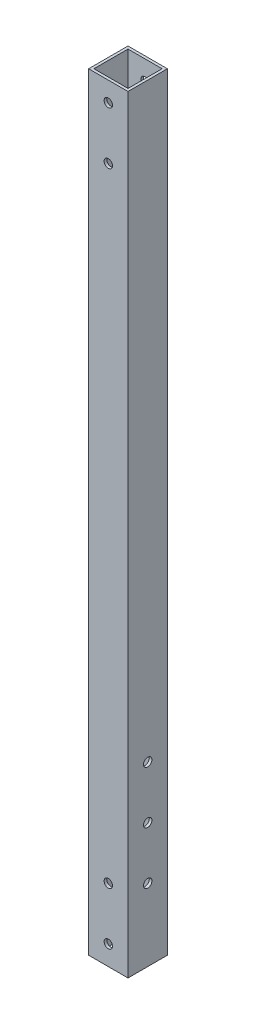
SolidWorks part; units mm, degrees
ref_plane "前视基准面" through (0, 0, 0) normal (0, 0, 1) x (1, 0, 0)
ref_plane "上视基准面" through (0, 0, 0) normal (0, 1, 0) x (1, 0, 0)
ref_plane "右视基准面" through (0, 0, 0) normal (1, 0, 0) x (0, 0, -1)
sketch "草图1" plane through (0, 0, 0) normal (0, 1, 0) x (1, 0, 0)
  line L1 (-7.5, -7.5) -> (7.5, -7.5)
  line L2 (-7.5, -7.5) -> (-7.5, 7.5)
  line L3 (-7.5, 7.5) -> (7.5, 7.5)
  line L4 (7.5, -7.5) -> (7.5, 7.5)
  line L5 (-7.5, -7.5) -> (7.5, 7.5) construction
  line L6 (-7.5, 7.5) -> (7.5, -7.5) construction
  point P0 (0, 0)
  dimension "D1" = 15
  dimension "D2" = 15
extrude "拉伸-薄壁1" add sketch "草图1" along normal blind 292.5 thin thin type one direction reverse wall 1
sketch "草图2" plane through (0, 0, 7.5) normal (0, 0, 1) x (1, 0, 0)
  line L0 (0, 0) -> (0, 292.5) construction
  line L1 (-7.5, 292.5) -> (7.5, 292.5) construction
  line L2 (-1000, 146.25) -> (49000, 146.25) construction
  line L3 (-7.5, 0) -> (7.5, 0) construction
  circle A0 centre (0, 7.5) radius 1.6
  circle A1 centre (0, 27.5) radius 1.6
  circle A2 centre (0, 265) radius 1.6
  circle A3 centre (0, 285) radius 1.6
  point P8 (0, 146.25)
  dimension "D1" = 3.2
  dimension "D2" = 7.5
  dimension "D3" = 20
extrude "切除-拉伸1" cut sketch "草图2" against normal through all
sketch "草图3" plane through (7.5, 0, 0) normal (1, 0, 0) x (0, 0, -1)
  line L0 (0, 0) -> (0, 292.5) construction
  line L1 (-7.5, 292.5) -> (7.5, 292.5) construction
  circle A0 centre (0, 27.5) radius 1.6
  circle A1 centre (0, 47.5) radius 1.6
  circle A2 centre (0, 67.5) radius 1.6
  dimension "D1" = 3.2
  dimension "D2" = 20
  dimension "D3" = 20
  dimension "D4" = 245
extrude "切除-拉伸2" cut sketch "草图3" against normal through all
